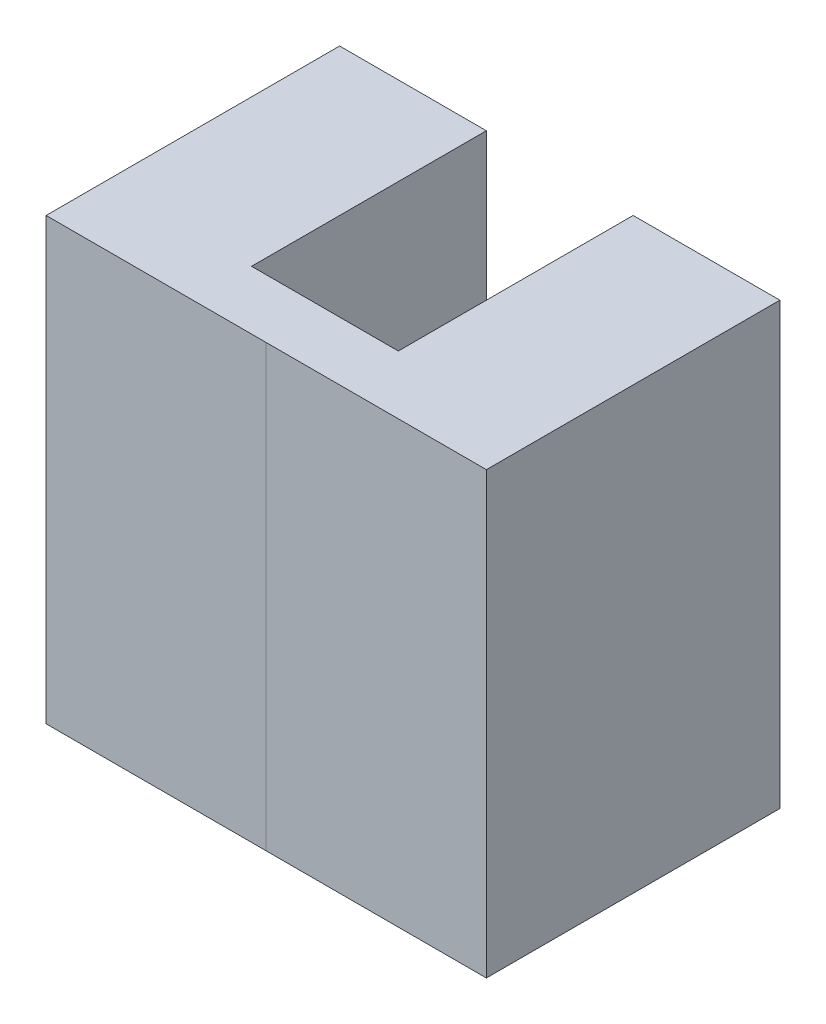
SolidWorks part; units mm, degrees
ref_plane "Front Plane" through (0, 0, 0) normal (0, 0, 1) x (1, 0, 0)
ref_plane "Top Plane" through (0, 0, 0) normal (0, 1, 0) x (1, 0, 0)
ref_plane "Right Plane" through (0, 0, 0) normal (1, 0, 0) x (0, 0, -1)
sketch "Sketch1" plane through (0, 0, 0) normal (0, 0, 1) x (1, 0, 0)
  line L1 (0, 0) -> (3, 0)
  line L2 (0, 0) -> (0, 3)
  line L3 (0, 3) -> (3, 3)
  line L4 (3, 0) -> (3, 3)
  dimension "D1" = 3
  dimension "D2" = 3
extrude "Boss-Extrude1" add sketch "Sketch1" along normal blind 2
sketch "Sketch2" plane through (0, 0, 0) normal (0, -1, 0) x (1, 0, 0)
  line L0 (0, 0) -> (3, 0) construction
  line L5 (1, 0) -> (2, 0)
  line L6 (1, 0) -> (1, 1.6)
  line L7 (1, 1.6) -> (2, 1.6)
  line L8 (2, 0) -> (2, 1.6)
  line L9 (0, 2) -> (0, 0) construction
  line L11 (0, 2) -> (3, 2) construction
  line L12 (3, 2) -> (3, 0) construction
  dimension "D1" = 1
  dimension "D2" = 0.4
  dimension "D3" = 1
extrude "Cut-Extrude1" cut sketch "Sketch2" against normal through all
sketch "Sketch3" plane through (0, 0, 2) normal (0, 0, 1) x (1, 0, 0)
  line L0 (1.5, 0) -> (1.5, 3)
  line L1 (0, 0) -> (3, 0) construction
  line L2 (3, 3) -> (0, 3) construction
split line "Split Line1"
